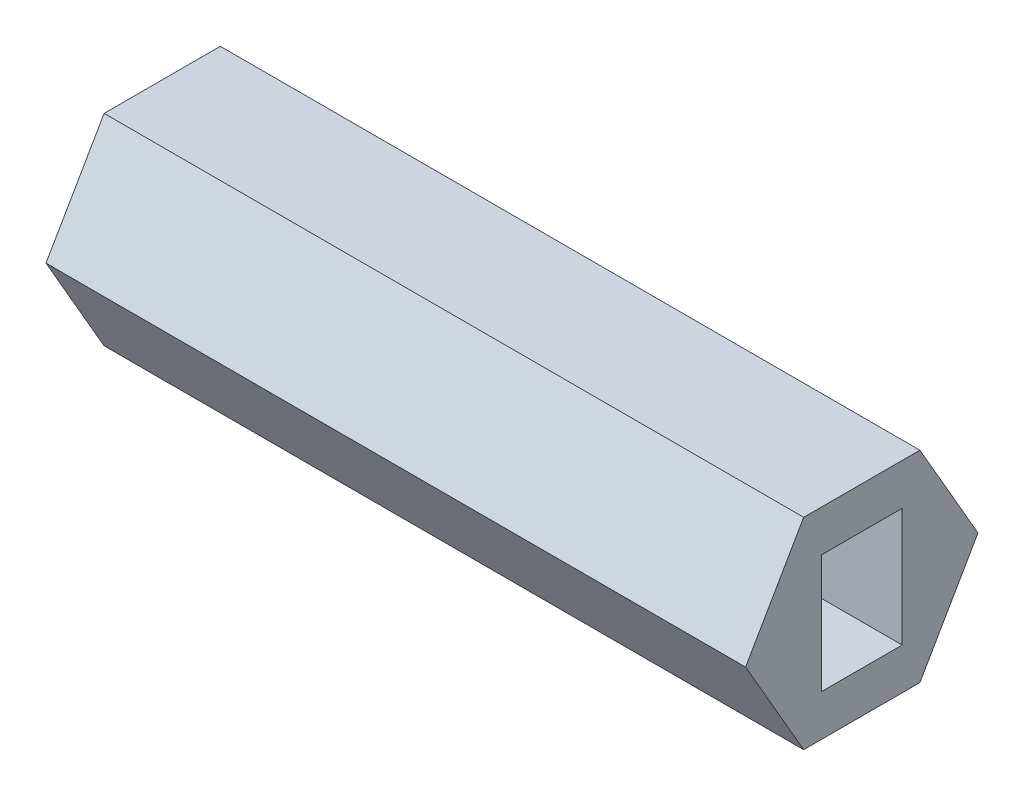
SolidWorks part; units mm, degrees
ref_plane "Front Plane" through (0, 0, 0) normal (0, 0, 1) x (1, 0, 0)
ref_plane "Top Plane" through (0, 0, 0) normal (0, 1, 0) x (1, 0, 0)
ref_plane "Right Plane" through (0, 0, 0) normal (1, 0, 0) x (0, 0, -1)
other "Graphic1"
sketch "Sketch1" plane through (0, 0, 0) normal (1, 0, 0) x (0, 0, -1)
  line L1 (-2.7424, 4.75) -> (-5.4848, 0)
  line L2 (-5.4848, 0) -> (-2.7424, -4.75)
  line L3 (-2.7424, -4.75) -> (2.7424, -4.75)
  line L4 (2.7424, -4.75) -> (5.4848, 0)
  line L5 (5.4848, 0) -> (2.7424, 4.75)
  line L6 (2.7424, 4.75) -> (-2.7424, 4.75)
  line L7 (1.905, -2.794) -> (-1.905, -2.794)
  line L8 (1.905, -2.794) -> (1.905, 2.794)
  line L9 (1.905, 2.794) -> (-1.905, 2.794)
  line L10 (-1.905, -2.794) -> (-1.905, 2.794)
  line L11 (1.905, -2.794) -> (-1.905, 2.794) construction
  line L12 (1.905, 2.794) -> (-1.905, -2.794) construction
  circle A0 centre (0, 0) radius 4.75 construction
  dimension "D1" = 9.5
  dimension "D2" = 5.588
  dimension "D3" = 3.81
extrude "Boss-Extrude1" add sketch "Sketch1" along normal blind 33.02
